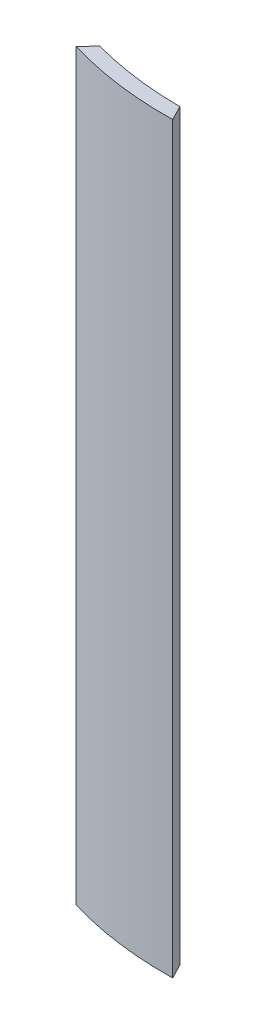
SolidWorks part; units mm, degrees
ref_plane "Front Plane" through (0, 0, 0) normal (0, 0, 1) x (1, 0, 0)
ref_plane "Top Plane" through (0, 0, 0) normal (0, 1, 0) x (1, 0, 0)
ref_plane "Right Plane" through (0, 0, 0) normal (1, 0, 0) x (0, 0, -1)
sketch "Sketch1" plane through (0, 0, 0) normal (0, 1, 0) x (1, 0, 0)
  line L0 (0, 0) -> (-1.2975, -4.7769) construction
  line L1 (0, 0) -> (0, -4.95) construction
  line L2 (0, 0) -> (-1.3964, -4.749) construction
  line L3 (0, 0) -> (0.1028, -4.9489) construction
  line L4 (-1.245, -4.5839) -> (-1.3964, -4.749)
  line L5 (0, -4.75) -> (0.1028, -4.9489)
  arc A0 (-1.3964, -4.749) -> (0.1028, -4.9489) centre (0, 0) ccw
  arc A1 (-1.245, -4.5839) -> (0, -4.75) centre (0, 0) ccw
  dimension "D1" = 9.9
  dimension "D3" = 16.385
  dimension "D4" = 4.75
  dimension "D6" = 0.2
  dimension "D7" = 4.95
  dimension "D2" = 15.196
  dimension "D5" = 16.385
extrude "Boss-Extrude1" add sketch "Sketch1" along normal blind 10
scale "Scale1" scale about centroid uniform scaling yes scale factor 5
